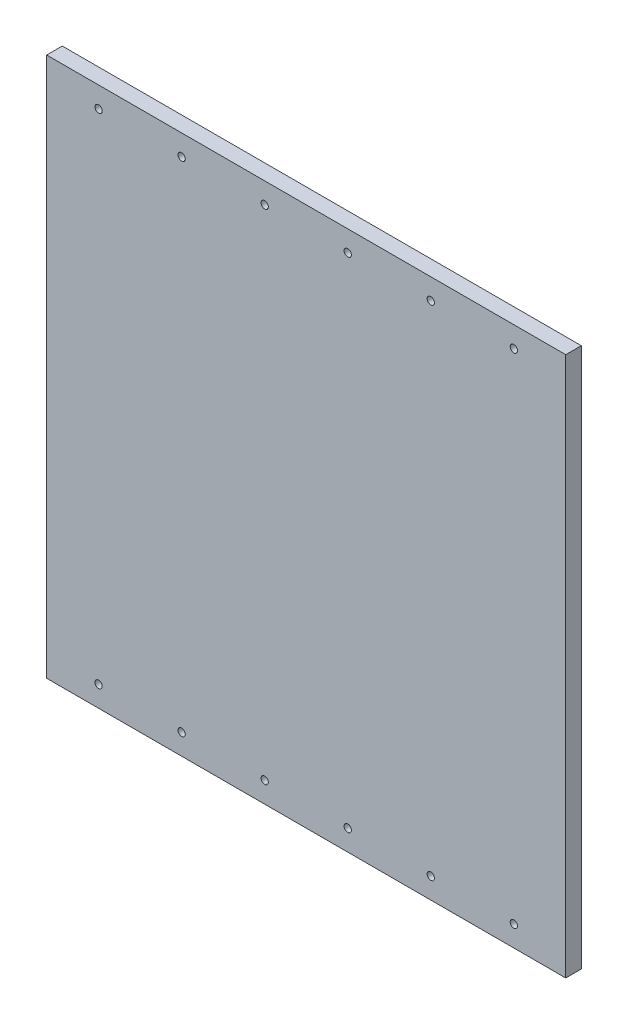
SolidWorks part; units mm, degrees
ref_plane "Plan de face" through (0, 0, 0) normal (0, 0, 1) x (1, 0, 0)
ref_plane "Plan de dessus" through (0, 0, 0) normal (0, 1, 0) x (1, 0, 0)
ref_plane "Plan de droite" through (0, 0, 0) normal (1, 0, 0) x (0, 0, -1)
sketch "Esquisse1" plane through (0, 0, 0) normal (0, 0, 1) x (1, 0, 0)
  line L1 (0, 0) -> (500, 0)
  line L2 (0, 0) -> (0, 520)
  line L3 (0, 520) -> (500, 520)
  line L4 (500, 0) -> (500, 520)
  dimension "D1" = 520
  dimension "D2" = 500
extrude "Boss.-Extru.1" add sketch "Esquisse1" along normal blind 15
sketch "Esquisse2" plane through (0, 0, 15) normal (0, 0, 1) x (1, 0, 0)
  line L0 (500, 500) -> (0, 500) construction
  line L1 (500, 0) -> (500, 520) construction
  line L2 (0, 520) -> (0, 0) construction
  line L3 (500, 520) -> (0, 520) construction
  line L4 (500, 260) -> (0, 260) construction
  line L5 (250, 260) -> (250, 520) construction
  line L6 (500, 20) -> (0, 20) construction
  circle A0 centre (210, 500) radius 3.5
  circle A1 centre (290, 500) radius 3.5
  circle A2 centre (130, 500) radius 3.5
  circle A3 centre (50, 500) radius 3.5
  circle A4 centre (450, 500) radius 3.5
  circle A5 centre (370, 500) radius 3.5
  circle A6 centre (370, 20) radius 3.5
  circle A7 centre (450, 20) radius 3.5
  circle A8 centre (50, 20) radius 3.5
  circle A9 centre (130, 20) radius 3.5
  circle A10 centre (290, 20) radius 3.5
  circle A11 centre (210, 20) radius 3.5
  dimension "D2" = 80
  dimension "D3" = 7
  dimension "D4" = 80
  dimension "D5" = 80
  dimension "D1" = 20
extrude "Enlèv. mat.-Extru.1" cut sketch "Esquisse2" against normal through all
